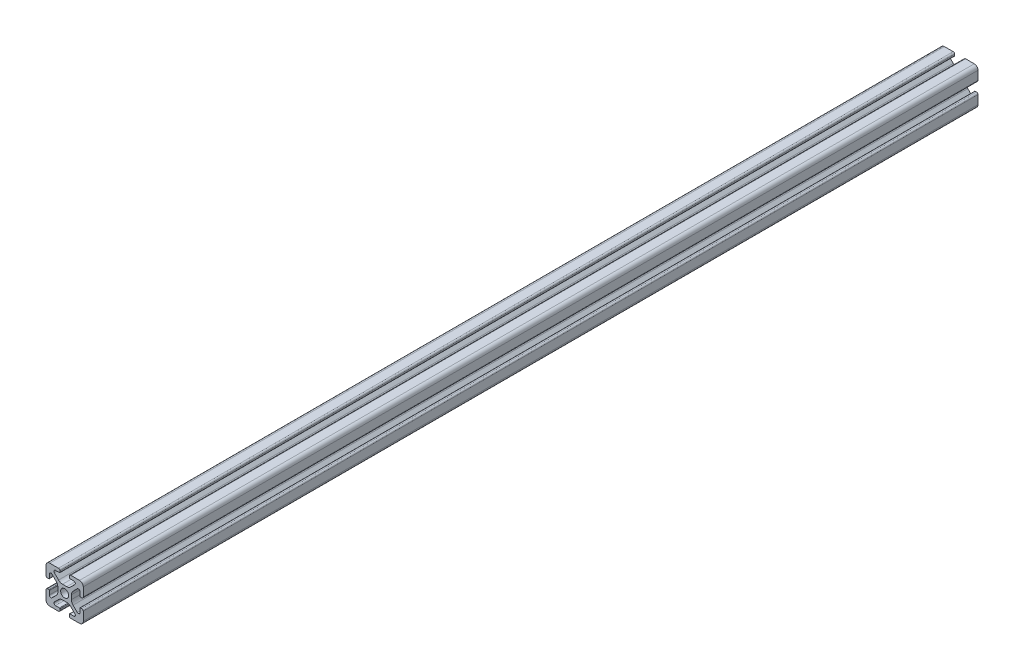
SolidWorks part; units mm, degrees
material "Alliage 1060"
ref_plane "Plan de face" through (0, 0, 0) normal (0, 0, 1) x (1, 0, 0)
ref_plane "Plan de dessus" through (0, 0, 0) normal (0, 1, 0) x (1, 0, 0)
ref_plane "Plan de droite" through (0, 0, 0) normal (1, 0, 0) x (0, 0, -1)
sketch "Esquisse1" plane through (0, 0, 0) normal (0, 0, 1) x (1, 0, 0)
  line L108 (-3.2559, 4.5287) -> (-5.5062, 6.779)
  line L109 (-4.9176, 8.2) -> (-2.8, 8.2)
  line L110 (-2.5, 8.5) -> (-2.5, 9.2)
  line L111 (-3.3, 10) -> (-8, 10)
  line L112 (-10, 8) -> (-10, 3.3)
  line L113 (-9.2, 2.5) -> (-8.5, 2.5)
  line L114 (-8.2, 2.8) -> (-8.2, 4.9176)
  line L115 (-6.779, 5.5062) -> (-4.5287, 3.2559)
  line L116 (-3.65, 1.1346) -> (-3.65, -1.1346)
  line L117 (-4.5287, -3.2559) -> (-6.779, -5.5062)
  line L118 (-8.2, -4.9176) -> (-8.2, -2.8)
  line L119 (-8.5, -2.5) -> (-9.2, -2.5)
  line L120 (-10, -3.3) -> (-10, -8)
  line L121 (-8, -10) -> (-3.3, -10)
  line L122 (-2.5, -9.2) -> (-2.5, -8.5)
  line L123 (-2.8, -8.2) -> (-4.9176, -8.2)
  line L124 (-5.5062, -6.779) -> (-3.2559, -4.5287)
  line L125 (-1.1346, -3.65) -> (1.1346, -3.65)
  line L126 (3.2559, -4.5287) -> (5.5062, -6.779)
  line L127 (4.9176, -8.2) -> (2.8, -8.2)
  line L128 (2.5, -8.5) -> (2.5, -9.2)
  line L129 (3.3, -10) -> (8, -10)
  line L130 (10, -8) -> (10, -3.3)
  line L131 (9.2, -2.5) -> (8.5, -2.5)
  line L132 (8.2, -2.8) -> (8.2, -4.9176)
  line L133 (6.779, -5.5062) -> (4.5287, -3.2559)
  line L134 (3.65, -1.1346) -> (3.65, 1.1346)
  line L135 (4.5287, 3.2559) -> (6.779, 5.5062)
  line L136 (8.2, 4.9176) -> (8.2, 2.8)
  line L137 (8.5, 2.5) -> (9.2, 2.5)
  line L138 (10, 3.3) -> (10, 8)
  line L139 (8, 10) -> (3.3, 10)
  line L140 (2.5, 9.2) -> (2.5, 8.5)
  line L141 (2.8, 8.2) -> (4.9176, 8.2)
  line L142 (5.5062, 6.779) -> (3.2559, 4.5287)
  line L143 (1.1346, 3.65) -> (-1.1346, 3.65)
  arc A42 (-2.15, 0) -> (2.15, 0) centre (0, 0) ccw
  arc A43 (2.15, 0) -> (-2.15, 0) centre (0, 0) ccw
  arc A108 (-4.9176, 8.2) -> (-5.5062, 6.779) centre (-4.9176, 7.3676) ccw
  arc A109 (-2.8, 8.2) -> (-2.5, 8.5) centre (-2.8, 8.5) ccw
  arc A110 (-2.5, 9.2) -> (-3.3, 10) centre (-3.3, 9.2) ccw
  arc A111 (-8, 10) -> (-10, 8) centre (-8, 8) ccw
  arc A112 (-10, 3.3) -> (-9.2, 2.5) centre (-9.2, 3.3) ccw
  arc A113 (-8.5, 2.5) -> (-8.2, 2.8) centre (-8.5, 2.8) ccw
  arc A114 (-6.779, 5.5062) -> (-8.2, 4.9176) centre (-7.3676, 4.9176) ccw
  arc A115 (-3.65, 1.1346) -> (-4.5287, 3.2559) centre (-6.65, 1.1346) ccw
  arc A116 (-4.5287, -3.2559) -> (-3.65, -1.1346) centre (-6.65, -1.1346) ccw
  arc A117 (-8.2, -4.9176) -> (-6.779, -5.5062) centre (-7.3676, -4.9176) ccw
  arc A118 (-8.2, -2.8) -> (-8.5, -2.5) centre (-8.5, -2.8) ccw
  arc A119 (-9.2, -2.5) -> (-10, -3.3) centre (-9.2, -3.3) ccw
  arc A120 (-10, -8) -> (-8, -10) centre (-8, -8) ccw
  arc A121 (-3.3, -10) -> (-2.5, -9.2) centre (-3.3, -9.2) ccw
  arc A122 (-2.5, -8.5) -> (-2.8, -8.2) centre (-2.8, -8.5) ccw
  arc A123 (-5.5062, -6.779) -> (-4.9176, -8.2) centre (-4.9176, -7.3676) ccw
  arc A124 (-1.1346, -3.65) -> (-3.2559, -4.5287) centre (-1.1346, -6.65) ccw
  arc A125 (3.2559, -4.5287) -> (1.1346, -3.65) centre (1.1346, -6.65) ccw
  arc A126 (4.9176, -8.2) -> (5.5062, -6.779) centre (4.9176, -7.3676) ccw
  arc A127 (2.8, -8.2) -> (2.5, -8.5) centre (2.8, -8.5) ccw
  arc A128 (2.5, -9.2) -> (3.3, -10) centre (3.3, -9.2) ccw
  arc A129 (8, -10) -> (10, -8) centre (8, -8) ccw
  arc A130 (10, -3.3) -> (9.2, -2.5) centre (9.2, -3.3) ccw
  arc A131 (8.5, -2.5) -> (8.2, -2.8) centre (8.5, -2.8) ccw
  arc A132 (6.779, -5.5062) -> (8.2, -4.9176) centre (7.3676, -4.9176) ccw
  arc A133 (3.65, -1.1346) -> (4.5287, -3.2559) centre (6.65, -1.1346) ccw
  arc A134 (4.5287, 3.2559) -> (3.65, 1.1346) centre (6.65, 1.1346) ccw
  arc A135 (8.2, 4.9176) -> (6.779, 5.5062) centre (7.3676, 4.9176) ccw
  arc A136 (8.2, 2.8) -> (8.5, 2.5) centre (8.5, 2.8) ccw
  arc A137 (9.2, 2.5) -> (10, 3.3) centre (9.2, 3.3) ccw
  arc A138 (10, 8) -> (8, 10) centre (8, 8) ccw
  arc A139 (3.3, 10) -> (2.5, 9.2) centre (3.3, 9.2) ccw
  arc A140 (2.5, 8.5) -> (2.8, 8.2) centre (2.8, 8.5) ccw
  arc A141 (5.5062, 6.779) -> (4.9176, 8.2) centre (4.9176, 7.3676) ccw
  arc A142 (1.1346, 3.65) -> (3.2559, 4.5287) centre (1.1346, 6.65) ccw
  arc A143 (-3.2559, 4.5287) -> (-1.1346, 3.65) centre (-1.1346, 6.65) ccw
extrude "Boss.-Extru.1" add sketch "Esquisse1" along normal blind 480
